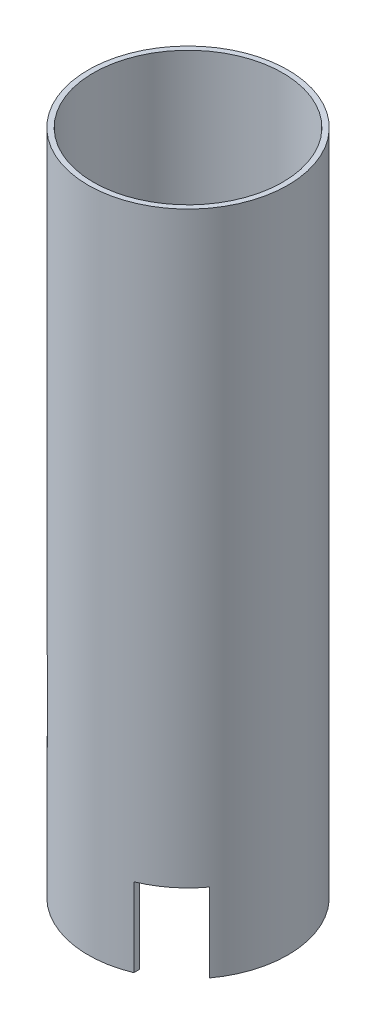
SolidWorks part; units mm, degrees
ref_plane "Front Plane" through (0, 0, 0) normal (0, 0, 1) x (1, 0, 0)
ref_plane "Top Plane" through (0, 0, 0) normal (0, 1, 0) x (1, 0, 0)
ref_plane "Right Plane" through (0, 0, 0) normal (1, 0, 0) x (0, 0, -1)
sketch "Sketch1" plane through (0, 0, 0) normal (0, 1, 0) x (1, 0, 0)
  circle A0 centre (0, 0) radius 36.5
  circle A1 centre (0, 0) radius 38.5
  dimension "D1" = 73
  dimension "D2" = 77
extrude "Boss-Extrude1" add sketch "Sketch1" along normal blind 257
sketch "Sketch3" plane through (0, 0, 0) normal (1, 0, 0) x (0, 0, -1)
  line L1 (-9.1083, 82.7957) -> (-30.1083, 82.7957)
  line L2 (-9.1083, 82.7957) -> (-9.1083, 51.7957)
  line L3 (-9.1083, 51.7957) -> (-30.1083, 51.7957)
  line L4 (-30.1083, 82.7957) -> (-30.1083, 51.7957)
  dimension "D1" = 21
  dimension "D2" = 31
extrude "Cut-Extrude1" cut sketch "Sketch3" against normal blind 50
sketch "Sketch8" plane through (0, 0, 0) normal (0, 0, 1) x (1, 0, 0)
  line L1 (14.7017, 30.3507) -> (31.0159, 30.3507)
  line L2 (14.7017, 30.3507) -> (14.7017, -1.9905)
  line L3 (14.7017, -1.9905) -> (31.0159, -1.9905)
  line L4 (31.0159, 30.3507) -> (31.0159, -1.9905)
extrude "Cut-Extrude4" cut sketch "Sketch8" along normal blind 40
sketch "Sketch9" plane through (0, 0, 0) normal (0, -1, 0) x (1, 0, 0)
  line L0 (0, 0) -> (-38.5, 0) construction
  arc A0 (14.7017, 35.5824) -> (31.0159, 22.8093) centre (0, 0) ccw construction
